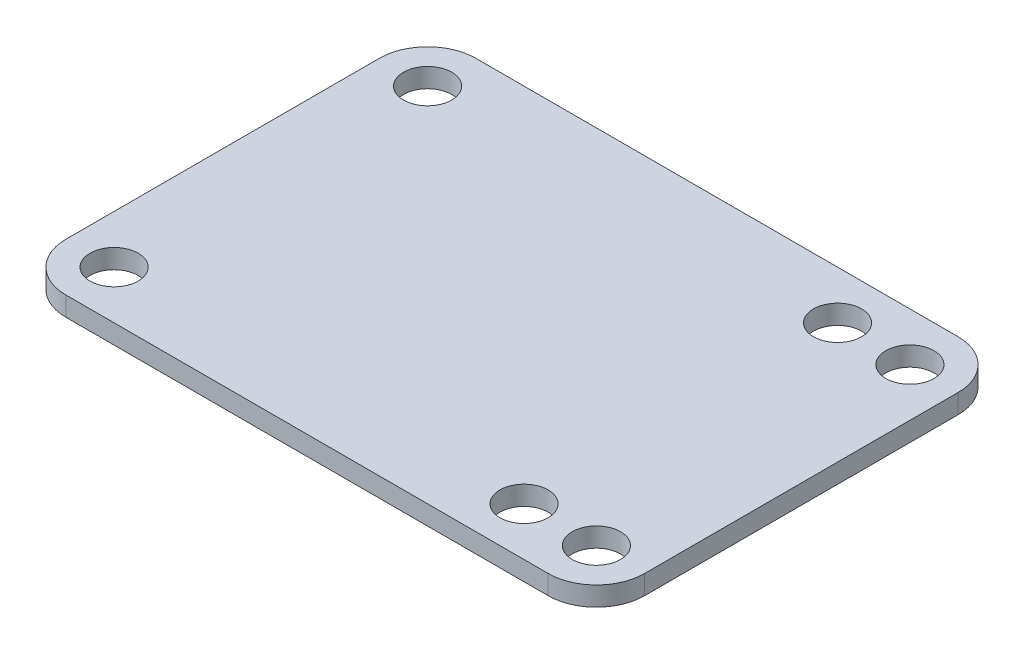
SolidWorks part; units mm, degrees
ref_plane "Front Plane" through (0, 0, 0) normal (0, 0, 1) x (1, 0, 0)
ref_plane "Top Plane" through (0, 0, 0) normal (0, 1, 0) x (1, 0, 0)
ref_plane "Right Plane" through (0, 0, 0) normal (1, 0, 0) x (0, 0, -1)
sketch "Main Lid Sketch" plane through (0, 0, 0) normal (0, 1, 0) x (1, 0, 0)
  line L0 (-38.1, 26.9875) -> (38.1, 26.9875)
  line L1 (38.1, 26.9875) -> (38.1, -26.9875)
  line L2 (38.1, -26.9875) -> (-38.1, -26.9875)
  line L3 (-38.1, -26.9875) -> (-38.1, 26.9875)
  point P7 (5.9144, 1.8569)
  dimension "D1" = 76.2
  dimension "D2" = 53.975
  dimension "D3" = 26.9875
  dimension "D4" = 38.1
extrude "Main Lid" add sketch "Main Lid Sketch" along normal blind 2.54
sketch "Hole Cut Sketch" plane through (0, 2.54, 0) normal (0, 1, 0) x (1, 0, 0)
  line L0 (-38.1, -26.9875) -> (38.1, -26.9875) construction
  line L1 (38.1, -26.9875) -> (38.1, 26.9875) construction
  line L2 (-38.1, 26.9875) -> (-38.1, -26.9875) construction
  line L3 (38.1, 26.9875) -> (-38.1, 26.9875) construction
  circle A0 centre (31.75, -20.6375) radius 3.175
  circle A1 centre (22.225, -20.6375) radius 3.175
  circle A2 centre (-31.75, -20.6375) radius 3.175
  circle A3 centre (-31.75, 20.6375) radius 3.175
  circle A4 centre (22.225, 20.6375) radius 3.175
  circle A5 centre (31.75, 20.6375) radius 3.175
  point P22 (24.3836, 21.6203)
  dimension "D1" = 6.35
  dimension "D2" = 6.35
  dimension "D3" = 6.35
  dimension "D4" = 6.35
  dimension "D5" = 6.35
  dimension "D6" = 6.35
  dimension "D7" = 6.35
  dimension "D8" = 6.35
  dimension "D9" = 6.35
  dimension "D10" = 6.35
  dimension "D11" = 9.525
  dimension "D12" = 6.35
  dimension "D13" = 6.35
  dimension "D14" = 6.35
  dimension "D15" = 6.35
  dimension "D16" = 9.525
  dimension "D17" = 6.35
  dimension "D18" = 6.35
extrude "Hole Cut" cut sketch "Hole Cut Sketch" against normal through all both and the other way through all
fillet "Corner Fillet" radius 6.35 4 edges at (-38.1, 1.27, 26.9875) (-38.1, 1.27, -26.9875) (38.1, 1.27, -26.9875) (38.1, 1.27, 26.9875)
equation "\"D3@Main Lid Sketch\" = \"D2@Main Lid Sketch\" * 0.5"
equation "\"D4@Main Lid Sketch\" = \"D1@Main Lid Sketch\" * 0.5"
equation "\"D2@Hole Cut Sketch\" = \"D1@Hole Cut Sketch\""
equation "\"D3@Hole Cut Sketch\" = \"D1@Hole Cut Sketch\""
equation "\"D4@Hole Cut Sketch\" = \"D1@Hole Cut Sketch\""
equation "\"D5@Hole Cut Sketch\" = \"D1@Hole Cut Sketch\""
equation "\"D6@Hole Cut Sketch\" = \"D1@Hole Cut Sketch\""
equation "\"D9@Hole Cut Sketch\" = \"D7@Hole Cut Sketch\""
equation "\"D10@Hole Cut Sketch\" = \"D7@Hole Cut Sketch\""
equation "\"D12@Hole Cut Sketch\" = \"D8@Hole Cut Sketch\""
equation "\"D13@Hole Cut Sketch\" = \"D8@Hole Cut Sketch\""
equation "\"D14@Hole Cut Sketch\" = \"D7@Hole Cut Sketch\""
equation "\"D15@Hole Cut Sketch\" = \"D7@Hole Cut Sketch\""
equation "\"D16@Hole Cut Sketch\" = \"D11@Hole Cut Sketch\""
equation "\"D17@Hole Cut Sketch\" = \"D12@Hole Cut Sketch\""
equation "\"D18@Hole Cut Sketch\" = \"D10@Hole Cut Sketch\""
